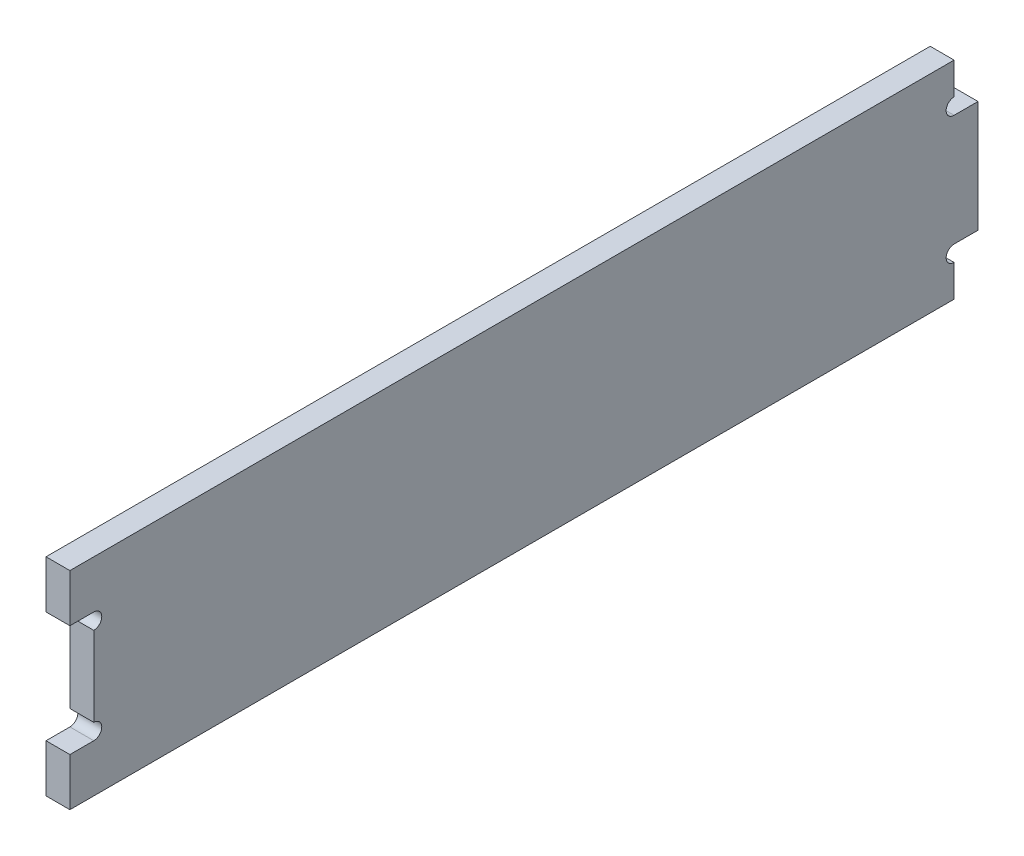
SolidWorks part; units mm, degrees
ref_plane "정면" through (0, 0, 0) normal (0, 0, 1) x (1, 0, 0)
ref_plane "윗면" through (0, 0, 0) normal (0, 1, 0) x (1, 0, 0)
ref_plane "우측면" through (0, 0, 0) normal (1, 0, 0) x (0, 0, -1)
sketch "스케치1" plane through (0, 0, 0) normal (1, 0, 0) x (0, 0, -1)
  line L1 (0, 0) -> (111, 0)
  line L2 (0, 0) -> (0, 26)
  line L3 (0, 26) -> (111, 26)
  line L4 (111, 0) -> (111, 26)
  dimension "D1" = 111
  dimension "D2" = 26
extrude "보스-돌출1" add sketch "스케치1" along normal blind 3
sketch "스케치2" plane through (3, 0, 0) normal (1, 0, 0) x (0, 0, -1)
  line L0 (111, 0) -> (111, 26) construction
  line L1 (111, 20) -> (114, 20)
  line L2 (111, 20) -> (111, 6)
  line L3 (111, 6) -> (114, 6)
  line L4 (114, 20) -> (114, 6)
  line L5 (111, 26) -> (0, 26) construction
  line L6 (0, 0) -> (111, 0) construction
  dimension "D1" = 6
  dimension "D2" = 6
  dimension "D3" = 3
extrude "보스-돌출2" add sketch "스케치2" against normal blind 3
sketch "스케치3" plane through (3, 0, 0) normal (1, 0, 0) x (0, 0, -1)
  line L0 (0, 26) -> (0, 0) construction
  line L1 (0, 20) -> (3, 20)
  line L2 (0, 20) -> (0, 6)
  line L3 (0, 6) -> (3, 6)
  line L4 (3, 20) -> (3, 6)
  line L5 (111, 26) -> (0, 26) construction
  line L6 (0, 0) -> (111, 0) construction
  dimension "D1" = 6
  dimension "D2" = 6
  dimension "D3" = 3
extrude "컷-돌출1" cut sketch "스케치3" against normal blind 5
sketch "스케치4" plane through (3, 0, 0) normal (1, 0, 0) x (0, 0, -1)
  line L0 (111, 20) -> (111, 26) construction
  line L1 (111, 0) -> (111, 6) construction
  line L2 (3, 6) -> (3, 20) construction
  circle A0 centre (111, 21) radius 1
  circle A1 centre (111, 5) radius 1
  circle A2 centre (3, 19) radius 1
  circle A3 centre (3, 7) radius 1
  dimension "D1" = 2
extrude "컷-돌출2" cut sketch "스케치4" against normal blind 10
